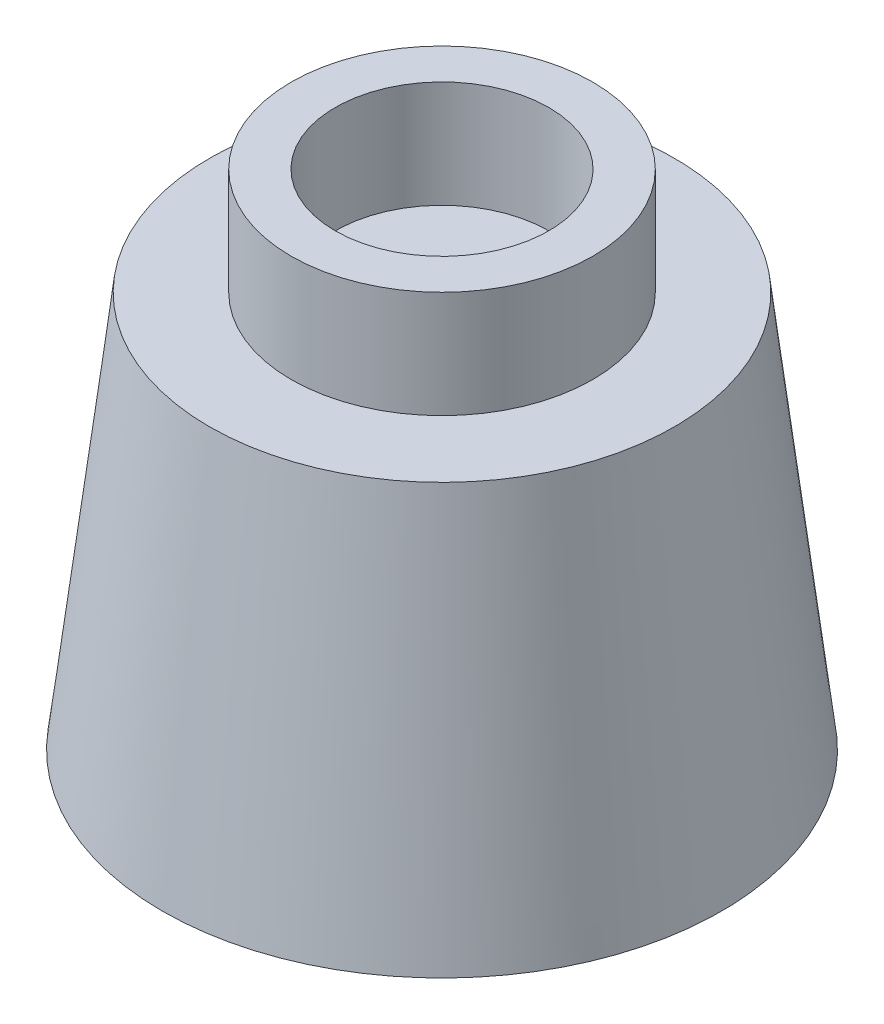
SolidWorks part; units mm, degrees
material "ABS"
ref_plane "Front Plane" through (0, 0, 0) normal (0, 0, 1) x (1, 0, 0)
ref_plane "Top Plane" through (0, 0, 0) normal (0, 1, 0) x (1, 0, 0)
ref_plane "Right Plane" through (0, 0, 0) normal (1, 0, 0) x (0, 0, -1)
sketch "Sketch1" plane through (0, 0, 0) normal (0, 1, 0) x (1, 0, 0)
  circle A0 centre (0, 0) radius 4.45
  dimension "D1" = 8.9
ref_plane "Plane1" through (0, 6.3, 0) normal (0, 1, 0) x (1, 0, 0)
sketch "Sketch2" plane through (0, 6.3, 0) normal (0, 1, 0) x (1, 0, 0)
  circle A0 centre (0, 0) radius 3.7
  dimension "D1" = 7.4
loft "Loft1" add profiles "Sketch1", "Sketch2"
sketch "Sketch3" plane through (0, 6.3, 0) normal (0, 1, 0) x (1, 0, 0)
  circle A0 centre (0, 0) radius 2.4
  circle A1 centre (0, 0) radius 1.7
  dimension "D1" = 4.8
  dimension "D2" = 0.7
extrude "Boss-Extrude1" add sketch "Sketch3" along normal blind 1.7
sketch "Sketch4" plane through (0, 0, 0) normal (0, -1, 0) x (1, 0, 0)
  circle A0 centre (0, 0) radius 3.4502
  circle A1 centre (0, 0) radius 4.45 construction
  dimension "D1" = 0.9998
extrude "Cut-Extrude1" cut sketch "Sketch4" against normal blind 2.4
sketch "Sketch5" plane through (0, 2.4, 0) normal (0, -1, 0) x (1, 0, 0)
  circle A0 centre (0, 0) radius 2.4502
  circle A1 centre (0, 0) radius 3.4502 construction
  dimension "D1" = 1
extrude "Cut-Extrude2" cut sketch "Sketch5" against normal offset from surface (3.1 mm away) 5.5 contours A0 up to face at (0, 0, -3.4502)
